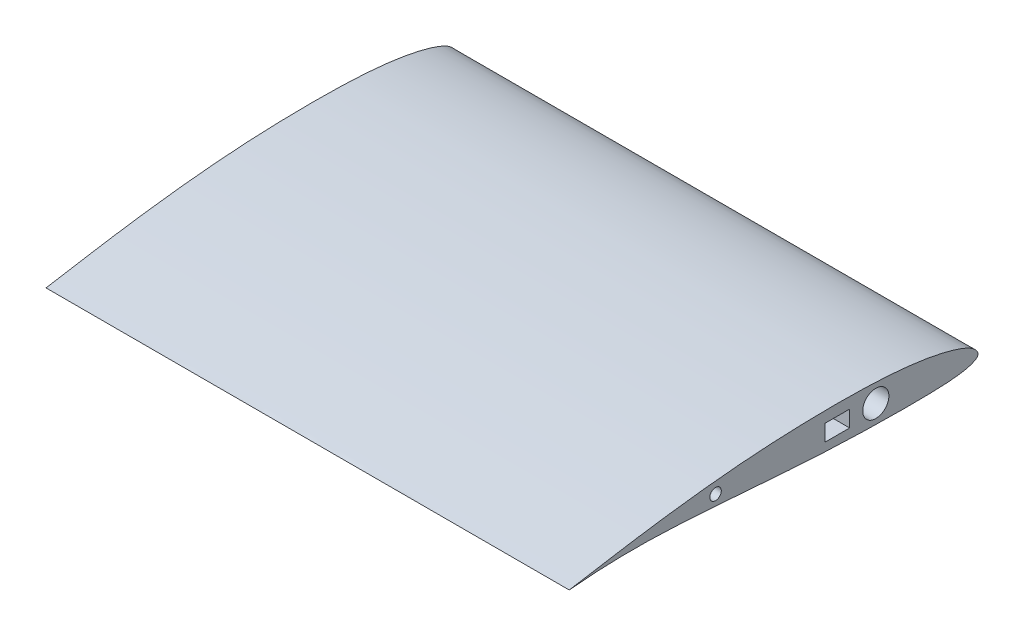
SolidWorks part; units mm, degrees
material "Foam"
ref_plane "Piano frontale" through (0, 0, 0) normal (0, 0, 1) x (1, 0, 0)
ref_plane "Piano superiore" through (0, 0, 0) normal (0, 1, 0) x (1, 0, 0)
ref_plane "Piano destro" through (0, 0, 0) normal (1, 0, 0) x (0, 0, -1)
curve "Curva1"
  spline degree 3 poles (0, 0.1724, 248.285) (0, -0.053, 250.4273) (0, 0.2462, 248.3284) (0, 0.5529, 246.6445) (0, 1.2459, 242.6221) (0, 2.0989, 237.7464) (0, 3.1818, 231.3634) (0, 4.2933, 223.9772) (0, 5.7312, 215.5604) (0, 7.1315, 206.3004) (0, 8.6324, 196.1631) (0, 10.1162, 185.3524) (0, 11.5493, 173.9891) (0, 12.8816, 162.1914) (0, 14.0593, 150.0724) (0, 15.0523, 137.7438) (0, 15.8256, 125.3116) (0, 16.3834, 112.8888) (0, 16.7267, 100.597) (0, 16.8648, 88.5669) (0, 16.792, 76.9314) (0, 16.4941, 65.8165) (0, 15.9609, 55.3329) (0, 15.1594, 45.573) (0, 14.0978, 36.6074) (0, 12.7884, 28.4972) (0, 11.2839, 21.2988) (0, 9.6413, 15.0749) (0, 7.9136, 9.8809) (0, 6.1182, 5.7699) (0, 4.2384, 2.7289) (0, 2.3057, 0.8126) (0, 0.7927, 0.0312) (0, -0.4105, -0.0213) (0, -1.7115, 0.4949) (0, -2.8658, 2.6253) (0, -4.0404, 5.6977) (0, -4.9287, 10.0719) (0, -5.5974, 15.6262) (0, -6.0122, 22.4122) (0, -6.265, 30.3619) (0, -6.3814, 39.3972) (0, -6.3554, 49.3987) (0, -6.2185, 60.2453) (0, -5.9476, 71.8018) (0, -5.5368, 83.9408) (0, -4.9386, 96.5461) (0, -4.1527, 109.5201) (0, -3.2196, 122.7671) (0, -2.1909, 136.1764) (0, -1.148, 149.6158) (0, -0.1602, 162.9314) (0, 0.706, 175.9537) (0, 1.3896, 188.4999) (0, 1.8332, 200.3712) (0, 1.9676, 211.3376) (0, 1.8232, 221.1842) (0, 1.4973, 229.6804) (0, 1.0741, 236.8065) (0, 0.6857, 242.1894) (0, 0.3087, 246.5181) (0, 0.1724, 248.285) (0, -0.053, 250.4273) (0, 0.2462, 248.3284) knots -0.014202 -0.006329 -0.001589 0 0.001576 0.006211 0.01368 0.023764 0.036307 0.051658 0.068045 0.086769 0.107053 0.128647 0.151303 0.174786 0.19886 0.223309 0.247929 0.272522 0.296848 0.320648 0.343669 0.365658 0.3864 0.405741 0.423561 0.439779 0.454311 0.467034 0.477831 0.486643 0.493542 0.498786 0.50271 0.50309 0.505896 0.510322 0.516831 0.525521 0.536535 0.549945 0.565696 0.583577 0.603379 0.624844 0.647727 0.671743 0.696673 0.722357 0.748609 0.77521 0.801891 0.828329 0.854175 0.879074 0.902636 0.924421 0.943939 0.960827 0.974827 0.985798 0.993671 0.998411 1 1.001576 1.006211 1.01368 periodic
sketch "Schizzo1" plane through (0, 0, 0) normal (1, 0, 0) x (0, 0, -1)
  line L0 (-250, 0) -> (0.0001, 0.0174) construction
  line L1 (0.0001, 0.0174) -> (-0.0034, 50.0174) construction
  line L2 (-62.4999, 16.3096) -> (-62.4999, -6.155) construction
  line L4 (-93.4999, 10.0773) -> (-78.4999, 10.0773)
  line L5 (-93.4999, 10.0773) -> (-93.4999, 0.0773)
  line L6 (-93.4999, 0.0773) -> (-78.4999, 0.0773)
  line L7 (-78.4999, 10.0773) -> (-78.4999, 0.0773)
  circle A0 centre (-62.4999, 5.0773) radius 8
  spline S0 degree 3 poles (-248.3284, 0.2462) (-250.4273, -0.053) (-248.285, 0.1724) (-246.5181, 0.3087) (-242.1894, 0.6857) (-236.8065, 1.0741) (-229.6804, 1.4973) (-221.1842, 1.8232) (-211.3376, 1.9676) (-200.3712, 1.8332) (-188.4999, 1.3896) (-175.9537, 0.706) (-162.9314, -0.1602) (-149.6158, -1.148) (-136.1764, -2.1909) (-122.7671, -3.2196) (-109.5201, -4.1527) (-96.5461, -4.9386) (-83.9408, -5.5368) (-71.8018, -5.9476) (-60.2453, -6.2185) (-49.3987, -6.3554) (-39.3972, -6.3814) (-30.3619, -6.265) (-22.4122, -6.0122) (-15.6262, -5.5974) (-10.0719, -4.9287) (-5.6977, -4.0404) (-2.6253, -2.8658) (-0.4949, -1.7115) (0.0213, -0.4105) (-0.0312, 0.7927) (-0.8126, 2.3057) (-2.7289, 4.2384) (-5.7699, 6.1182) (-9.8809, 7.9136) (-15.0749, 9.6413) (-21.2988, 11.2839) (-28.4972, 12.7884) (-36.6074, 14.0978) (-45.573, 15.1594) (-55.3329, 15.9609) (-65.8165, 16.4941) (-76.9314, 16.792) (-88.5669, 16.8648) (-100.597, 16.7267) (-112.8888, 16.3834) (-125.3116, 15.8256) (-137.7438, 15.0523) (-150.0724, 14.0593) (-162.1914, 12.8816) (-173.9891, 11.5493) (-185.3524, 10.1162) (-196.1631, 8.6324) (-206.3004, 7.1315) (-215.5604, 5.7312) (-223.9772, 4.2933) (-231.3634, 3.1818) (-237.7464, 2.0989) (-242.6221, 1.2459) (-246.6445, 0.5529) (-248.3284, 0.2462) (-250.4273, -0.053) (-248.285, 0.1724) knots -0.01368 -0.006211 -0.001576 0 0.001589 0.006329 0.014202 0.025173 0.039173 0.056061 0.075579 0.097364 0.120926 0.145825 0.171671 0.198109 0.22479 0.251391 0.277643 0.303327 0.328257 0.352273 0.375156 0.396621 0.416423 0.434304 0.450055 0.463465 0.474479 0.483169 0.489678 0.494104 0.49691 0.49729 0.501214 0.506458 0.513357 0.522169 0.532966 0.545689 0.560221 0.576439 0.594259 0.6136 0.634342 0.656331 0.679352 0.703152 0.727478 0.752071 0.776691 0.80114 0.825214 0.848697 0.871353 0.892947 0.913231 0.931955 0.948342 0.963693 0.976236 0.98632 0.993789 0.998424 1 1.001589 1.006329 1.014202 only from (-250, 0) to (-250, 0) construction
  spline S1 degree 3 poles (-248.3284, 0.2462) (-250.4273, -0.053) (-248.285, 0.1724) (-246.5181, 0.3087) (-242.1894, 0.6857) (-236.8065, 1.0741) (-229.6804, 1.4973) (-221.1842, 1.8232) (-211.3376, 1.9676) (-200.3712, 1.8332) (-188.4999, 1.3896) (-175.9537, 0.706) (-162.9314, -0.1602) (-149.6158, -1.148) (-136.1764, -2.1909) (-122.7671, -3.2196) (-109.5201, -4.1527) (-96.5461, -4.9386) (-83.9408, -5.5368) (-71.8018, -5.9476) (-60.2453, -6.2185) (-49.3987, -6.3554) (-39.3972, -6.3814) (-30.3619, -6.265) (-22.4122, -6.0122) (-15.6262, -5.5974) (-10.0719, -4.9287) (-5.6977, -4.0404) (-2.6253, -2.8658) (-0.4949, -1.7115) (0.0213, -0.4105) (-0.0312, 0.7927) (-0.8126, 2.3057) (-2.7289, 4.2384) (-5.7699, 6.1182) (-9.8809, 7.9136) (-15.0749, 9.6413) (-21.2988, 11.2839) (-28.4972, 12.7884) (-36.6074, 14.0978) (-45.573, 15.1594) (-55.3329, 15.9609) (-65.8165, 16.4941) (-76.9314, 16.792) (-88.5669, 16.8648) (-100.597, 16.7267) (-112.8888, 16.3834) (-125.3116, 15.8256) (-137.7438, 15.0523) (-150.0724, 14.0593) (-162.1914, 12.8816) (-173.9891, 11.5493) (-185.3524, 10.1162) (-196.1631, 8.6324) (-206.3004, 7.1315) (-215.5604, 5.7312) (-223.9772, 4.2933) (-231.3634, 3.1818) (-237.7464, 2.0989) (-242.6221, 1.2459) (-246.6445, 0.5529) (-248.3284, 0.2462) (-250.4273, -0.053) (-248.285, 0.1724) knots -0.01368 -0.006211 -0.001576 0 0.001589 0.006329 0.014202 0.025173 0.039173 0.056061 0.075579 0.097364 0.120926 0.145825 0.171671 0.198109 0.22479 0.251391 0.277643 0.303327 0.328257 0.352273 0.375156 0.396621 0.416423 0.434304 0.450055 0.463465 0.474479 0.483169 0.489678 0.494104 0.49691 0.49729 0.501214 0.506458 0.513357 0.522169 0.532966 0.545689 0.560221 0.576439 0.594259 0.6136 0.634342 0.656331 0.679352 0.703152 0.727478 0.752071 0.776691 0.80114 0.825214 0.848697 0.871353 0.892947 0.913231 0.931955 0.948342 0.963693 0.976236 0.98632 0.993789 0.998424 1 1.001589 1.006329 1.014202 only from (-250, 0) to (-250, 0)
  point P12 (-78.4999, 5.0773)
  dimension "D3" = 16
  dimension "D1" = 50
  dimension "D2" = 62.5
  dimension "D4" = 15
  dimension "D5" = 10
  dimension "D6" = 16
extrude "CorpoFoam" add sketch "Schizzo1" along normal blind 320
sketch "Schizzo2" plane through (0, 0, 0) normal (-1, 0, 0) x (0, 0, 1)
  line L1 (160.4999, 6.0773) -> (62.4999, 5.0773) construction
  circle A0 centre (160.4999, 6.0773) radius 3.5
  dimension "D1" = 7
  dimension "D2" = 1
  dimension "D3" = 98
extrude "AggancioPernoSinistro" cut sketch "Schizzo2" against normal blind 15
sketch "Schizzo3" plane through (320, 0, 0) normal (1, 0, 0) x (0, 0, -1)
  circle A0 centre (-160.4999, 6.0773) radius 3.5
  dimension "D1" = 7
extrude "AggancioPernoDestro" cut sketch "Schizzo3" against normal blind 15
